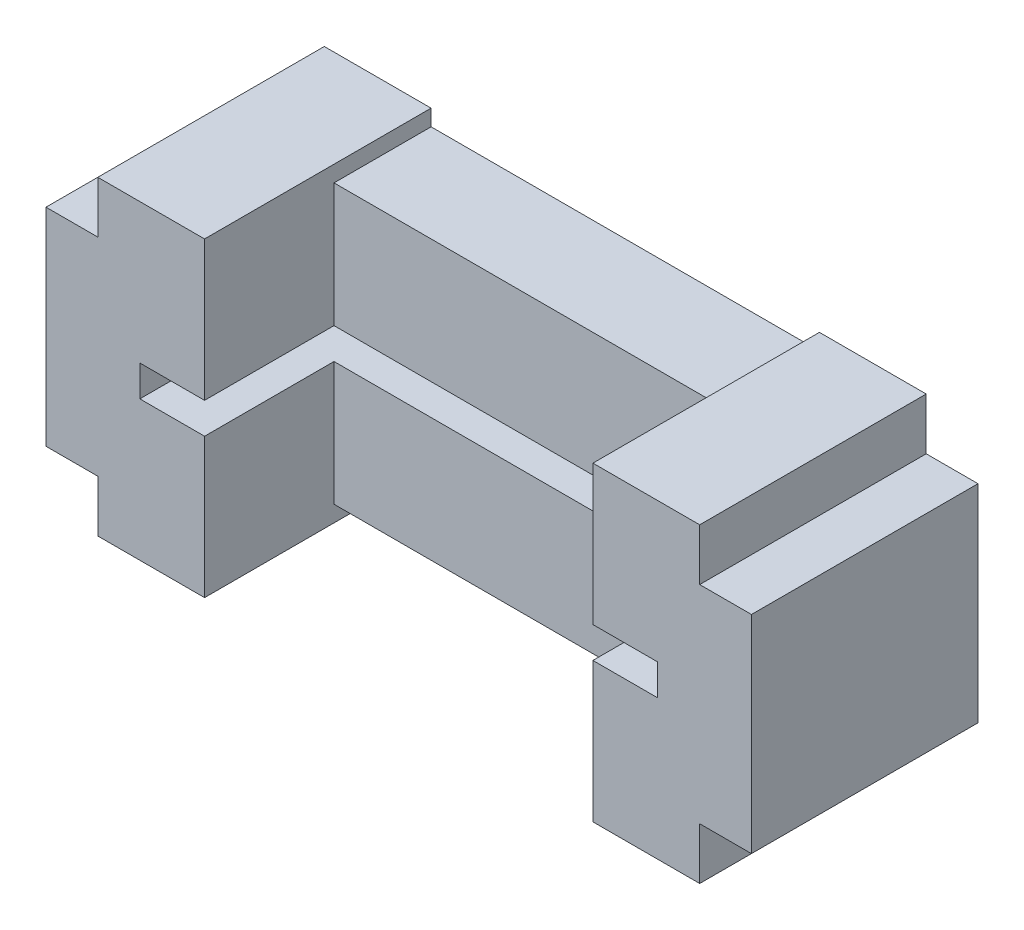
SolidWorks part; units mm, degrees
ref_plane "Front Plane" through (0, 0, 0) normal (0, 0, 1) x (1, 0, 0)
ref_plane "Top Plane" through (0, 0, 0) normal (0, 1, 0) x (1, 0, 0)
ref_plane "Right Plane" through (0, 0, 0) normal (1, 0, 0) x (0, 0, -1)
sketch "Sketch1" plane through (0, 0, 0) normal (0, 0, 1) x (1, 0, 0)
  line L1 (-29.5275, -15.24) -> (29.5275, -15.24)
  line L2 (-34.6075, -10.16) -> (-34.6075, 10.16)
  line L3 (-29.5275, 15.24) -> (29.5275, 15.24)
  line L4 (34.6075, -10.16) -> (34.6075, 10.16)
  line L9 (-34.6075, 10.16) -> (-29.5275, 10.16)
  line L10 (-29.5275, 15.24) -> (-29.5275, 10.16)
  line L13 (-34.6075, -10.16) -> (-29.5275, -10.16)
  line L14 (-29.5275, -15.24) -> (-29.5275, -10.16)
  line L17 (34.6075, -10.16) -> (29.5275, -10.16)
  line L18 (29.5275, -15.24) -> (29.5275, -10.16)
  line L21 (34.6075, 10.16) -> (29.5275, 10.16)
  line L22 (29.5275, 15.24) -> (29.5275, 10.16)
  point P0 (0, 0)
  point P2 (0, 15.24)
  point P4 (-34.6075, 0)
  dimension "D1" = 69.215
  dimension "D2" = 30.48
  dimension "D3" = 5.08
extrude "Boss-Extrude1" add sketch "Sketch1" along normal blind 9.525
sketch "Sketch3" plane through (0, 0, 9.525) normal (0, 0, 1) x (1, 0, 0)
  line L0 (29.5275, 15.24) -> (-29.5275, 15.24) construction
  line L1 (-29.5275, 15.24) -> (-19.05, 15.24)
  line L2 (-34.6075, 10.16) -> (-34.6075, -10.16)
  line L3 (-29.5275, -15.24) -> (-19.05, -15.24)
  line L4 (-19.05, 15.24) -> (-19.05, 1.524)
  line L5 (-29.5275, -15.24) -> (29.5275, -15.24) construction
  line L6 (0, 0) -> (0, 15.24) construction
  line L7 (-19.05, 1.524) -> (-25.4, 1.524)
  line L9 (-19.05, -1.524) -> (-25.4, -1.524)
  line L10 (-25.4, 1.524) -> (-25.4, -1.524)
  line L11 (-19.05, -1.524) -> (-19.05, -15.24)
  line L12 (19.05, -1.524) -> (19.05, -15.24)
  line L13 (25.4, 1.524) -> (25.4, -1.524)
  line L14 (19.05, -1.524) -> (25.4, -1.524)
  line L15 (19.05, 1.524) -> (25.4, 1.524)
  line L16 (19.05, 15.24) -> (19.05, 1.524)
  line L17 (29.5275, -15.24) -> (19.05, -15.24)
  line L18 (34.6075, 10.16) -> (34.6075, -10.16)
  line L19 (29.5275, 15.24) -> (19.05, 15.24)
  line L20 (-34.6075, 10.16) -> (-34.6075, -10.16) construction
  line L21 (29.5275, -15.24) -> (29.5275, -10.16) construction
  line L24 (-34.6075, 10.16) -> (-29.5275, 10.16)
  line L25 (-29.5275, 15.24) -> (-29.5275, 10.16)
  line L26 (-29.5275, -10.16) -> (-34.6075, -10.16)
  line L27 (-29.5275, -10.16) -> (-29.5275, -15.24)
  line L32 (34.6075, -10.16) -> (29.5275, -10.16)
  line L33 (29.5275, -15.24) -> (29.5275, -10.16)
  line L34 (29.5275, -10.16) -> (34.6075, -10.16) construction
  line L37 (34.6075, 10.16) -> (29.5275, 10.16)
  line L38 (29.5275, 15.24) -> (29.5275, 10.16)
  line L39 (34.6075, -10.16) -> (34.6075, 10.16) construction
  point P12 (-25.4, 0)
  dimension "D1" = 6.35
  dimension "D2" = 3.048
  dimension "D4" = 19.05
extrude "Boss-Extrude2" add sketch "Sketch3" along normal blind 12.7
sketch "Sketch4" plane through (0, 0, 9.525) normal (0, 0, 1) x (1, 0, 0)
  line L1 (-25.4, -1.524) -> (25.4, -1.524)
  line L2 (-25.4, -1.524) -> (-25.4, 1.524)
  line L3 (-25.4, 1.524) -> (25.4, 1.524)
  line L4 (25.4, -1.524) -> (25.4, 1.524)
extrude "Cut-Extrude1" cut sketch "Sketch4" against normal blind 6.096
sketch "Sketch5" plane through (0, 0, 9.525) normal (0, 0, 1) x (1, 0, 0)
  line L0 (19.05, 15.24) -> (-19.05, 15.24) construction
  line L1 (-19.05, 15.24) -> (19.05, 15.24)
  line L2 (-19.05, 15.24) -> (-19.05, 13.6525)
  line L3 (-19.05, 13.6525) -> (19.05, 13.6525)
  line L4 (19.05, 15.24) -> (19.05, 13.6525)
  line L5 (0, 0) -> (12.7, 0) construction
  line L6 (19.05, -15.24) -> (19.05, -13.6525)
  line L7 (-19.05, -13.6525) -> (19.05, -13.6525)
  line L8 (-19.05, -15.24) -> (-19.05, -13.6525)
  line L9 (-19.05, -15.24) -> (19.05, -15.24)
  line L10 (-19.05, 1.524) -> (-19.05, 15.24) construction
  point P6 (0, 13.6525)
  dimension "D1" = 1.5875
extrude "Cut-Extrude2" cut sketch "Sketch5" against normal through all both and the other way through all
